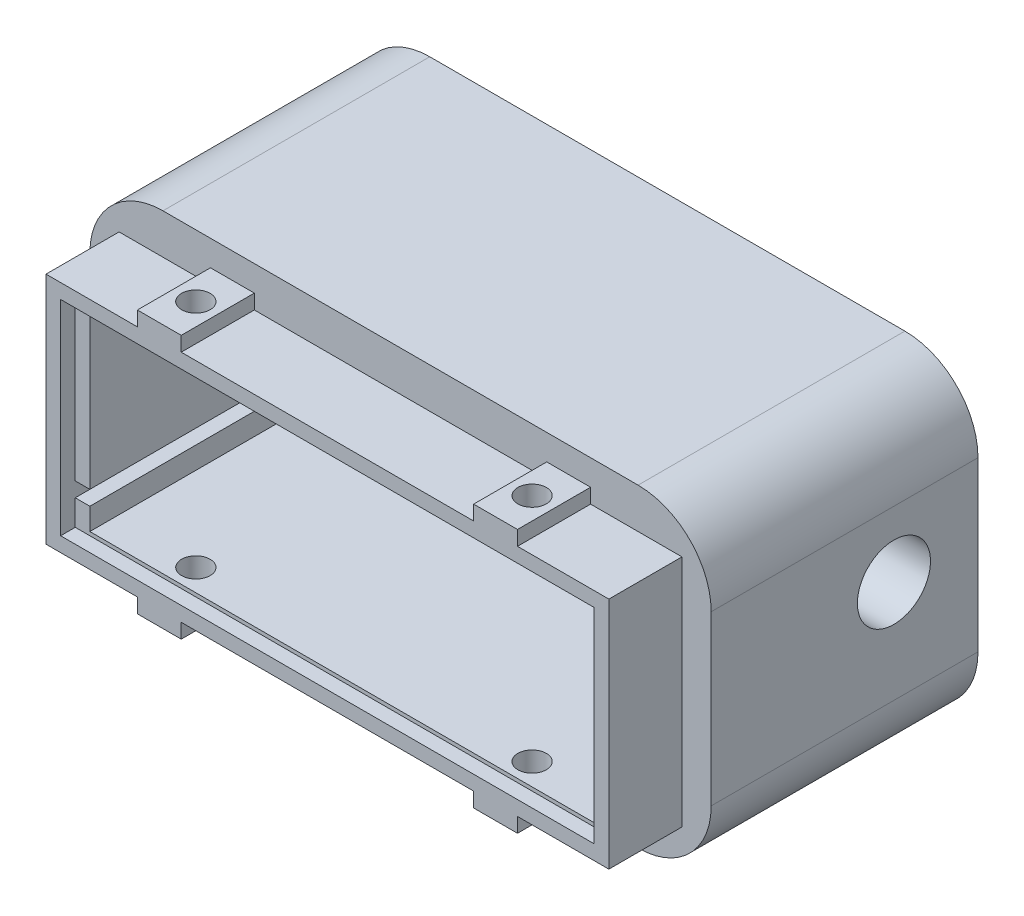
SolidWorks part; units mm, degrees
ref_plane "Přední rovina" through (0, 0, 0) normal (0, 0, 1) x (1, 0, 0)
ref_plane "Horní rovina" through (0, 0, 0) normal (0, 1, 0) x (1, 0, 0)
ref_plane "Pravá rovina" through (0, 0, 0) normal (1, 0, 0) x (0, 0, -1)
sketch "Skica1" plane through (0, 0, 0) normal (0, 0, 1) x (1, 0, 0)
  line L0 (-34.5, 13.5) -> (-34.5, -13.5)
  line L1 (-32.5, 21.5) -> (32.5, 21.5)
  line L2 (-42.5, 11.5) -> (-42.5, -11.5)
  line L3 (-32.5, -21.5) -> (32.5, -21.5)
  line L4 (42.5, 11.5) -> (42.5, -11.5)
  line L5 (-42.5, 21.5) -> (42.5, -21.5) construction
  line L6 (-42.5, -21.5) -> (42.5, 21.5) construction
  line L7 (-34.5, -13.5) -> (34.5, -13.5)
  line L8 (34.5, 13.5) -> (34.5, -13.5)
  line L9 (-34.5, 13.5) -> (34.5, 13.5)
  line L10 (0, 0) -> (0, -31.0939)
  line L11 (-42.5, -21.5) -> (42.5, -21.5) construction
  line L12 (-36.5, -10.5) -> (36.5, -10.5)
  line L13 (-36.5, -10.5) -> (-36.5, -8.5)
  line L14 (-36.5, -8.5) -> (36.5, -8.5)
  line L15 (36.5, -10.5) -> (36.5, -8.5)
  line L16 (-36.5, -10.5) -> (36.5, -8.5) construction
  line L17 (-36.5, -8.5) -> (36.5, -10.5) construction
  line L18 (42.5, 21.5) -> (42.5, -21.5) construction
  line L19 (-42.5, 21.5) -> (42.5, 21.5) construction
  line L20 (-42.5, 21.5) -> (-42.5, -21.5) construction
  arc A0 (32.5, -21.5) -> (42.5, -11.5) centre (32.5, -11.5) ccw
  arc A1 (32.5, 21.5) -> (42.5, 11.5) centre (32.5, 11.5) cw
  arc A2 (-32.5, 21.5) -> (-42.5, 11.5) centre (-32.5, 11.5) ccw
  arc A3 (-42.5, -11.5) -> (-32.5, -21.5) centre (-32.5, -11.5) ccw
  point P0 (0, 0)
  point P12 (0, -9.5)
  dimension "D7" = 10
  dimension "D1" = 85
  dimension "D2" = 43
  dimension "D4" = 3
  dimension "D5" = 2
  dimension "D6" = 73
  dimension "D3" = 8
extrude "Přidat vysunutím1" add sketch "Skica1" along normal blind 46.5
sketch "Skica2" plane through (0, 0, 0) normal (0, 0, -1) x (-1, 0, 0)
  line L0 (0, 0) -> (-32.8766, 0)
  line L1 (-42.5, 11.5) -> (42.5, 11.5)
  line L2 (-42.5, 11.5) -> (-42.5, -11.5)
  line L3 (-42.5, -11.5) -> (42.5, -11.5)
  line L4 (42.5, 11.5) -> (42.5, -11.5)
  line L5 (-42.5, 11.5) -> (42.5, -11.5) construction
  line L6 (-42.5, -11.5) -> (42.5, 11.5) construction
  line L7 (10, 7.5) -> (-10, 7.5)
  line L8 (10, 7.5) -> (10, -7.5)
  line L9 (10, -7.5) -> (-10, -7.5)
  line L10 (-10, 7.5) -> (-10, -7.5)
  line L11 (10, 7.5) -> (-10, -7.5) construction
  line L12 (10, -7.5) -> (-10, 7.5) construction
  line L13 (0, 0) -> (0, 5.0474)
  line L18 (-30.5, 7.5) -> (-23.5, -7.5) construction
  line L19 (-30.5, -7.5) -> (-23.5, 7.5) construction
  point P0 (0, 0)
  point P7 (0, 0)
  point P14 (-27, 0)
  dimension "D1" = 20
  dimension "D2" = 15
extrude "Přidat vysunutím2" add sketch "Skica2" against normal blind 6.5
sketch "Skica3" plane through (0, 0, 6.5) normal (0, 0, 1) x (1, 0, 0)
  line L0 (-19, 0) -> (19, 0)
  line L1 (0, 0) -> (0, 6.1845)
  dimension "D1" = 19
hole_wizard "Válcové zahloubení pro M6 šrouby s válcovou hlavou zaoblenou1" positions "Skica4" profile "Skica5" counterbore size "M6" standard "ANSI Metric" end condition up to next
sketch "Skica4" plane through (0, 0, 6.5) normal (0, 0, 1) x (1, 0, 0)
  point P0 (-19, 0)
  point P3 (19, 0)
sketch "Skica5" plane through (-19, 0, 6.5) normal (1, 0, 0) x (0, -1, 0)
  line L0 (0, 0) -> (0, 6.5)
  line L1 (0, 6.5) -> (3.3, 6.5)
  line L3 (3.3, 6.5) -> (3.3, 4.6)
  line L4 (3.3, 4.6) -> (6.5, 4.6)
  line L5 (6.5, 4.6) -> (6.5, 0)
  line L7 (6.5, 0) -> (0, 0)
  line L11 (0, -6.35) -> (0, 107.95) construction
  dimension "Průměr díry skrz" = 6.6
  dimension "Hloubka díry skrz" = 6.5
  dimension "Průměr válcového zahloubení" = 13
  dimension "Hloubka válcového zahloubení" = 4.6
sketch "Skica6" plane through (34.5, 0, 0) normal (-1, 0, 0) x (0, 0, 1)
  line L0 (6.5, -8.5) -> (6.5, 13.5)
  line L1 (46.5, 13.5) -> (0, 13.5) construction
  line L2 (6.5, 2.5) -> (11.5, 2.5)
  circle A0 centre (11.5, 2.5) radius 5
  dimension "D1" = 5
extrude "Odebrat vysunutím1" cut sketch "Skica6" against normal through all
sketch "Skica7" plane through (0, 0, 46.5) normal (0, 0, 1) x (1, 0, 0)
  line L1 (-36.5, 14) -> (36.5, 14)
  line L2 (-36.5, 14) -> (-36.5, -14)
  line L3 (-36.5, -14) -> (36.5, -14)
  line L4 (36.5, 14) -> (36.5, -14)
  line L5 (-36.5, 14) -> (36.5, -14) construction
  line L6 (-36.5, -14) -> (36.5, 14) construction
  point P0 (0, 0)
  dimension "D1" = 73
  dimension "D2" = 28
extrude "Odebrat vysunutím2" cut sketch "Skica7" against normal blind 2
sketch "Skica8" plane through (0, 0, 46.5) normal (0, 0, 1) x (1, 0, 0)
  line L0 (-38.5, 16) -> (38.5, 16)
  line L1 (-36.5, 14) -> (36.5, 14)
  line L2 (-36.5, 14) -> (-36.5, -14)
  line L3 (-36.5, -14) -> (36.5, -14)
  line L4 (36.5, 14) -> (36.5, -14)
  line L5 (-36.5, 14) -> (36.5, -14) construction
  line L6 (-36.5, -14) -> (36.5, 14) construction
  line L7 (38.5, 16) -> (38.5, -16)
  line L8 (-38.5, -16) -> (38.5, -16)
  line L9 (-38.5, 16) -> (-38.5, -16)
  line L10 (-48.5, 26) -> (-48.5, -26)
  line L11 (-48.5, -26) -> (48.5, -26)
  line L12 (48.5, 26) -> (48.5, -26)
  line L13 (-48.5, 26) -> (48.5, 26)
  point P0 (0, 0)
  line M13 (-32.5, -21.5) -> (32.5, -21.5)
  arc M14 (32.5, -21.5) -> (42.5, -11.5) centre (32.5, -11.5) ccw
  line M15 (42.5, -11.5) -> (42.5, 11.5)
  arc M16 (42.5, 11.5) -> (32.5, 21.5) centre (32.5, 11.5) ccw
  line M17 (32.5, 21.5) -> (-32.5, 21.5)
  arc M18 (-32.5, 21.5) -> (-42.5, 11.5) centre (-32.5, 11.5) ccw
  line M19 (-42.5, 11.5) -> (-42.5, -11.5)
  arc M20 (-42.5, -11.5) -> (-32.5, -21.5) centre (-32.5, -11.5) ccw
  dimension "D1" = 2
  dimension "D2" = 10
extrude "Odebrat vysunutím5" cut sketch "Skica8" against normal blind 10 contours L13 L10 L11 L12 M13 M20 M19 M18 M17 M16 M15 M14 | L9 L0 L7 L8 M20 M13 M14 M15 M16 M17 M18 M19
sketch "Skica9" plane through (0, 16, 0) normal (0, 1, 0) x (1, 0, 0)
  line L0 (38.5, -41.5) -> (-38.5, -41.5)
  line L1 (38.5, -36.5) -> (38.5, -46.5) construction
  line L2 (-38.5, -36.5) -> (-38.5, -46.5) construction
  line L3 (-38.5, -46.5) -> (38.5, -46.5) construction
  line L4 (26, -36.5) -> (20, -36.5)
  line L5 (26, -36.5) -> (26, -46.5)
  line L6 (26, -46.5) -> (20, -46.5)
  line L7 (20, -36.5) -> (20, -46.5)
  line L8 (26, -36.5) -> (20, -46.5) construction
  line L9 (26, -46.5) -> (20, -36.5) construction
  line L10 (0, -41.5) -> (0, -45.9436)
  line L11 (-26, -46.5) -> (-20, -46.5)
  line L12 (-26, -36.5) -> (-26, -46.5)
  line L13 (-26, -36.5) -> (-20, -36.5)
  line L14 (-20, -36.5) -> (-20, -46.5)
  point P6 (23, -41.5)
  point P13 (0, -41.5)
  line M6 (-38.5, -46.5) -> (38.5, -46.5)
  line M8 (38.5, -36.5) -> (-38.5, -36.5)
  dimension "D1" = 6
  dimension "D2" = 20
extrude "Přidat vysunutím3" add sketch "Skica9" along normal blind 2 contours L14 L0 L12 M6 | L14 L12 L0 M8 | L0 L7 L5 M6 | L7 L0 L5 M8
ref_plane "Rovina3" through (0, 0, 0) normal (0, -1, 0) x (-1, 0, 0)
mirror "Zrcadlit1" about plane through (0, 0, 0) normal (0, -1, 0) of "Přidat vysunutím3"
sketch "Skica10" plane through (0, -18, 0) normal (0, -1, 0) x (1, 0, 0)
  line L0 (20, 46.5) -> (23, 46.5)
  line L1 (20, 46.5) -> (26, 46.5) construction
  line L2 (23, 46.5) -> (23, 36.5)
  line L3 (26, 36.5) -> (20, 36.5) construction
  line L4 (0, 0) -> (0, 61.6703)
  point P5 (23, 41.5)
  point P13 (-23, 41.5)
hole_wizard "Díry pro kolík, velikost mm1" positions "Skica11" profile "Skica12" hole size "Ø3.0" standard "ANSI Metric"
sketch "Skica11" plane through (0, -18, 0) normal (0, -1, 0) x (-1, 0, 0)
  point P0 (-23, -41.5)
  point P3 (23, -41.5)
sketch "Skica12" plane through (23, -18, 41.5) normal (1, 0, 0) x (0, 0, -1)
  line L0 (0, 0) -> (0, 36)
  line L1 (0, 36) -> (1.95, 36)
  line L2 (1.95, 36) -> (1.95, 0)
  line L5 (1.95, 0) -> (0, 0)
  line L11 (0, -6.35) -> (0, 107.95) construction
  dimension "Průměr díry skrz" = 3.9
  dimension "Hloubka díry skrz" = 36
mirror "Zrcadlit2" about plane through (0, 0, 0) normal (0, -1, 0) of "Díry pro kolík, velikost mm1"
